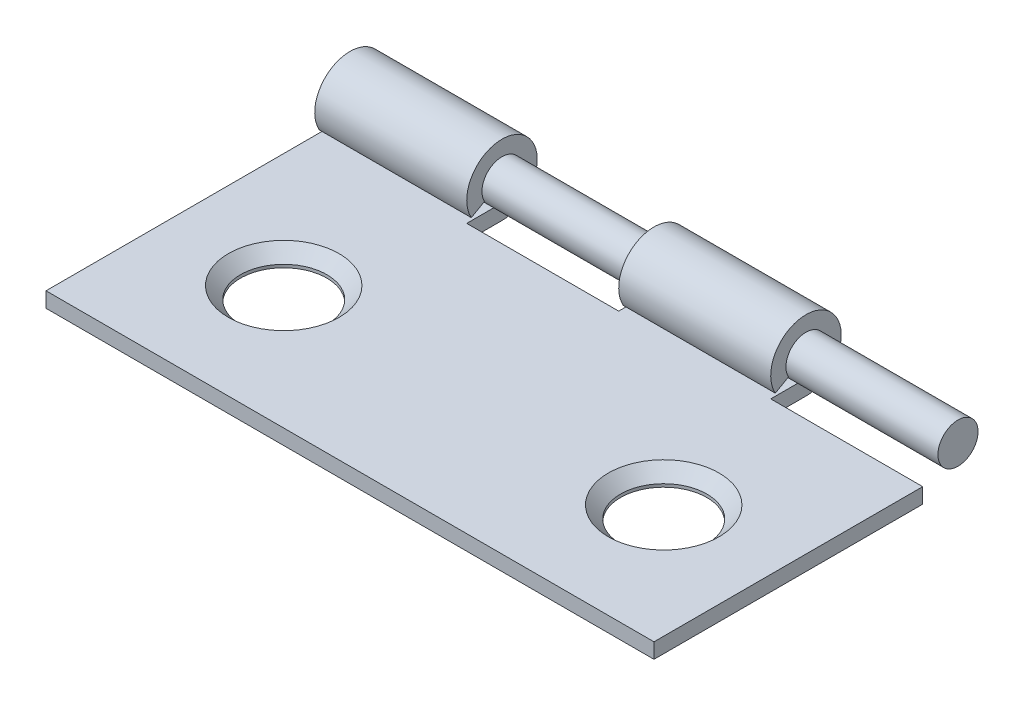
SolidWorks part; units mm, degrees
ref_plane "Front Plane" through (0, 0, 0) normal (0, 0, 1) x (1, 0, 0)
ref_plane "Top Plane" through (0, 0, 0) normal (0, 1, 0) x (1, 0, 0)
ref_plane "Right Plane" through (0, 0, 0) normal (1, 0, 0) x (0, 0, -1)
sketch "Sketch1" plane through (0, 0, 0) normal (0, 1, 0) x (1, 0, 0)
  line L0 (-12.7, 0) -> (12.7, 0) construction
  line L1 (-12.7, -12.7) -> (-12.7, 12.7) construction
  line L2 (-12.7, -12.7) -> (-7.9248, -12.7) construction
  line L4 (-7.9248, -12.7) -> (7.9502, -12.7) construction
  line L5 (12.7254, -12.7) -> (12.7254, -7.5438) construction
  line L6 (7.9502, -12.7) -> (12.7254, -12.7) construction
  line L7 (-12.7, 12.7) -> (-7.9248, 12.7) construction
  line L8 (-7.9248, 12.7) -> (7.9502, 12.7) construction
  line L9 (7.9502, 12.7) -> (23.8252, 12.7) construction
  line L10 (23.8252, 12.7) -> (28.6004, 12.7) construction
  line L11 (7.9502, -9.8552) -> (7.9502, -5.2324) construction
  line L12 (7.9502, -7.5438) -> (12.7254, -7.5438) construction
  point P3 (7.9502, -9.3472)
  point P4 (0, 0)
  point P8 (-12.7, 0)
  point P17 (-6.35, 0)
  point P21 (7.9502, -7.5438)
  dimension "Frame Leaf Height" = 25.4
  dimension "Overall Width" = 25.4
  dimension "Hole to End 1" = 4.7752
  dimension "Hole to End 2" = 4.7752
  dimension "D1" = 4.7752
  dimension "D2" = 4.7752
  dimension "D4" = 15.875
  dimension "D6" = 15.875
  dimension "Knuckle Length" = 6.35
  dimension "Hole Chamfer Dia" = 4.6228
  dimension "Hole Center to Pin" = 7.5438
  dimension "Door Leaf Height" = 25.4254
  dimension "Mounting Hole Diameter" = 3.6068
  dimension "D3" = 15.875
  dimension "Frame Leaf Width" = 12.7
  dimension "Door Leaf Width" = 12.7
sketch "Sketch2" plane through (0, 0, 0) normal (1, 0, 0) x (0, 0, -1)
  line L2 (0, -1.4732) -> (0, -0.8382) construction
  line L4 (0, 0.8382) -> (0, -0.8382) construction
  point P8 (0, 0)
  dimension "Leaf Thickness" = 0.635
  dimension "Pin Diameter" = 1.6764
sketch "Sketch3" plane through (0, 0, 0) normal (1, 0, 0) x (0, 0, -1)
  line L3 (0, 0) -> (-1.4732, -0.8382) construction
  line L4 (0, -1.4732) -> (-12.7, -1.4732)
  line L5 (-12.7, -1.4732) -> (-12.7, -0.8382)
  line L7 (-12.7, -0.8382) -> (0, -0.8382)
  line L8 (-12.7, 0) -> (12.7, 0) construction
  line L9 (-0.7285, -0.4145) -> (-1.2805, -0.7285)
  line L11 (-1.4732, 0) -> (-1.4732, -0.8382) construction
  circle A4 centre (0, 0) radius 0.8382 construction
  circle A5 centre (0, 0) radius 1.4732 construction
  arc A8 (-0.7285, -0.4145) -> (0, -0.8382) centre (0, 0) cw
  arc A9 (-1.2805, -0.7285) -> (0, -1.4732) centre (0, 0) cw
  point P0 (-1.2805, -0.7285)
  point P13 (-0.7285, -0.4145)
extrude "Boss-Extrude1" add sketch "Sketch3" along normal mid plane 25.4
sketch "Sketch4" plane through (0, 0, 0) normal (0, 1, 0) x (1, 0, 0)
  line L0 (-12.7, -1.4732) -> (12.7, -1.4732) construction
  line L1 (-12.7, -1.4732) -> (12.7, -1.4732) construction
  line L2 (12.7, 1.4732) -> (-12.7, 1.4732) construction
  line L3 (12.7, 1.4732) -> (-12.7, 1.4732) construction
  line L4 (-6.35, -1.4732) -> (-6.35, 1.4732)
  line L6 (-6.35, 1.4732) -> (0, 1.4732)
  line L7 (0, -1.4732) -> (-6.35, -1.4732)
  line L8 (0, 1.4732) -> (0, -1.4732)
  point P8 (-6.35, 0)
  dimension "D1" = 6.35
extrude "Cut-Extrude1" cut sketch "Sketch4" against normal through all both and the other way through all
pattern_linear "LPattern1" count 6 spacing 12.7 along (1, 0, 0) of "Cut-Extrude1"
sketch "Sketch5" plane through (0, -0.8382, 0) normal (0, 1, 0) x (1, 0, 0)
  line L0 (7.9502, -7.5438) -> (-7.9248, -7.5438) construction
  line L1 (0, -7.5438) -> (0, -12.7) construction
  line L2 (-7.9248, -7.5438) -> (-7.9248, -12.7) construction
  line L3 (12.7, -12.7) -> (-12.7, -12.7) construction
  circle A0 centre (7.9502, -7.5438) radius 2.3114
  circle A2 centre (-7.9248, -7.5438) radius 2.3114
extrude "Cut-Extrude2" cut sketch "Sketch5" against normal through all draft 45
sketch "Sketch9" plane through (0, 0, 0) normal (0, 1, 0) x (1, 0, 0)
  circle A0 centre (7.9502, -7.5438) radius 1.8034
  circle A2 centre (-7.9248, -7.5438) radius 1.8034
  dimension "D1" = 3.6068
extrude "Cut-Extrude3" cut sketch "Sketch9" against normal through all both and the other way through all
sketch "Sketch6" plane through (0, 0, 0) normal (1, 0, 0) x (0, 0, -1)
  circle A0 centre (0, 0) radius 0.8382
  dimension "D1" = 1.6764
extrude "Boss-Extrude2" add sketch "Sketch6" along normal mid plane 25.4 separate body
equation "\"Hole Chamfer Dia@Sketch1\"=\"Mounting Hole Diameter@Sketch1\"+.04"
equation "\"D1@Sketch9\"=\"Mounting Hole Diameter@Sketch1\""
equation "\"Hole to End 2@Sketch1\"=\"Hole to End 1@Sketch1\""
equation "\"Knuckle Length@Sketch1\"=\"Frame Leaf Height@Sketch1\" / 4"
equation "\"D3@Sketch7\"=\"Leaf Thickness@Sketch2\""
equation "\"D2@Sketch7\"=\"Overall Width@Sketch1\""
equation "\"D1@Sketch7\"=\"Pin Diameter@Sketch2\""
equation "\"D1@Boss-Extrude2\" = \"Frame Leaf Height@Sketch1\""
equation "\"D1@Sketch6\"=\"Pin Diameter@Sketch2\""
equation "\"D3@LPattern1\"=\"Knuckle Length@Sketch1\"*2"
equation "\"D1@Sketch4\"=\"Knuckle Length@Sketch1\""
equation "\"D1@Boss-Extrude1\" = \"Frame Leaf Height@Sketch1\""
equation "\"D6@Sketch1\"=\"D4@Sketch1\""
equation "\"D2@Sketch1\"=\"Hole to End 2@Sketch1\""
equation "\"D1@Sketch1\"=\"Hole to End 1@Sketch1\""
